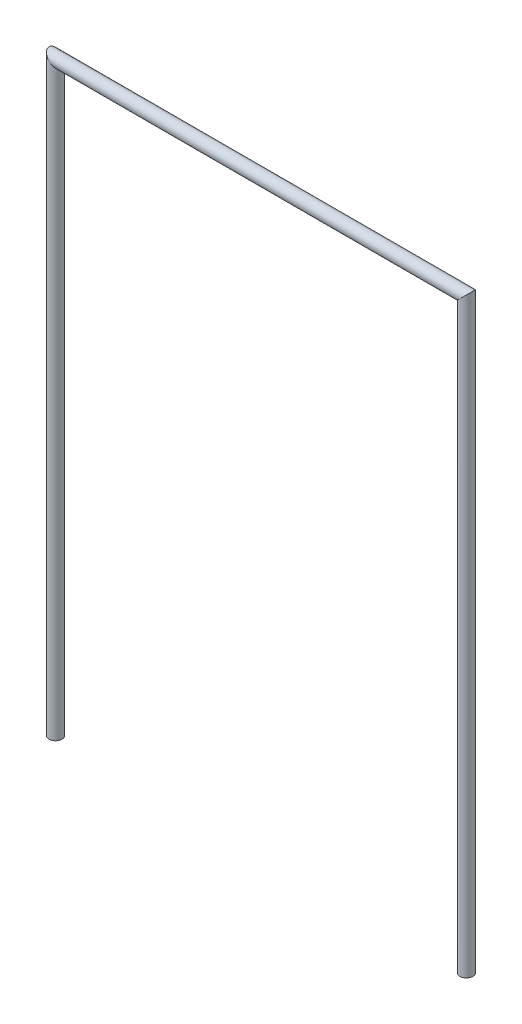
SolidWorks part; units mm, degrees
material "ASTM A36 Steel"
ref_plane "Front Plane" through (0, 0, 0) normal (0, 0, 1) x (1, 0, 0)
ref_plane "Top Plane" through (0, 0, 0) normal (0, 1, 0) x (1, 0, 0)
ref_plane "Right Plane" through (0, 0, 0) normal (1, 0, 0) x (0, 0, -1)
sketch "Sketch1" plane through (0, 0, 0) normal (0, 0, 1) x (1, 0, 0)
  line L0 (0, 0) -> (0, 10000)
  line L1 (0, 10000) -> (7000, 10000)
  line L2 (7000, 10000) -> (7000, 0)
  dimension "D1" = 10000
  dimension "D2" = 7000
other "Pipe xx strong PIPE XXS 8(1)"
ref_plane "Plane2" through (0, 0, 0) normal (0, 1, 0) x (-1, 0, 0)
sketch "Sketch14" plane through (0, 0, 0) normal (0, 1, 0) x (-1, 0, 0)
  circle A0 centre (0, 0) radius 87.3125
  circle A1 centre (0, 0) radius 109.5375
  point P3 (0, 0)
  dimension "In_dia" = 174.625
  dimension "Out_dia" = 219.075
